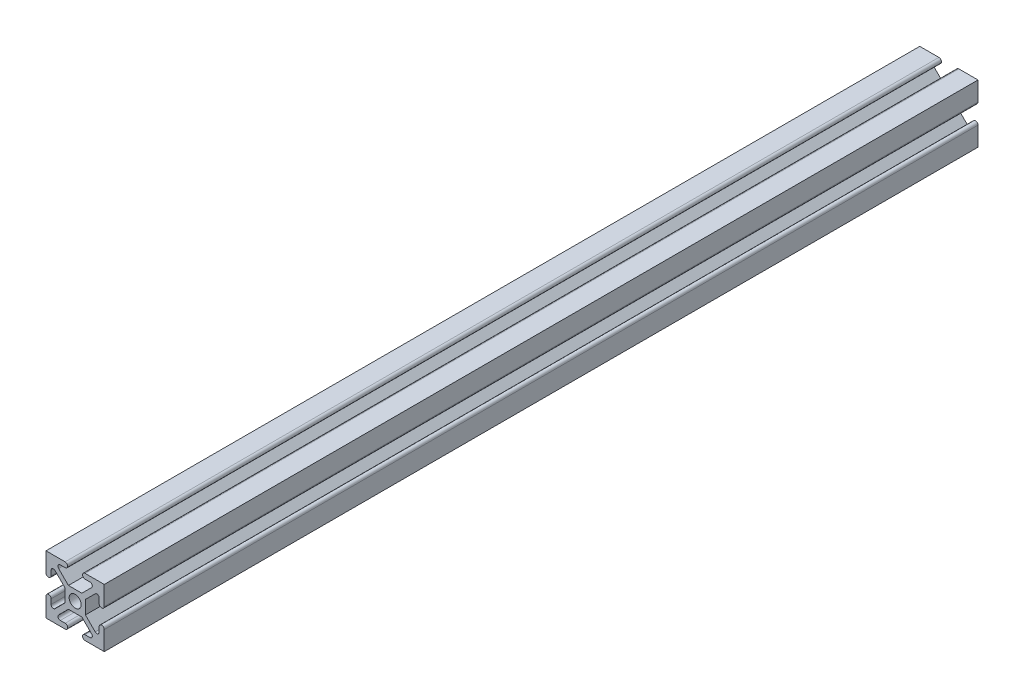
SolidWorks part; units mm, degrees
material "1060 Alloy"
ref_plane "Front Plane" through (0, 0, 0) normal (0, 0, 1) x (1, 0, 0)
ref_plane "Top Plane" through (0, 0, 0) normal (0, 1, 0) x (1, 0, 0)
ref_plane "Right Plane" through (0, 0, 0) normal (1, 0, 0) x (0, 0, -1)
sketch "Sketch1" plane through (0, 0, 0) normal (0, 0, 1) x (1, 0, 0)
  line L2 (-12.7, -12.7) -> (-4.3434, -12.7)
  line L3 (-4.3434, -10.4902) -> (-6.4748, -10.4902)
  line L4 (-7.1932, -8.7558) -> (-2.9332, -4.4958)
  line L5 (-2.9332, -4.4958) -> (2.9332, -4.4958)
  line L6 (2.9332, -4.4958) -> (7.1932, -8.7558)
  line L7 (6.4748, -10.4902) -> (4.3434, -10.4902)
  line L8 (4.3434, -12.7) -> (12.7, -12.7)
  line L11 (12.7, -12.7) -> (12.7, -4.3434)
  line L12 (10.4902, -4.3434) -> (10.4902, -6.4748)
  line L13 (8.7558, -7.1932) -> (4.4958, -2.9332)
  line L14 (4.4958, -2.9332) -> (4.4958, 2.9332)
  line L15 (4.4958, 2.9332) -> (8.7558, 7.1932)
  line L16 (10.4902, 6.4748) -> (10.4902, 4.3434)
  line L17 (12.7, 4.3434) -> (12.7, 12.7)
  line L20 (12.7, 12.7) -> (4.3434, 12.7)
  line L21 (4.3434, 10.4902) -> (6.4748, 10.4902)
  line L22 (7.1932, 8.7558) -> (2.9332, 4.4958)
  line L23 (2.9332, 4.4958) -> (-2.9332, 4.4958)
  line L24 (-2.9332, 4.4958) -> (-7.1932, 8.7558)
  line L25 (-6.4748, 10.4902) -> (-4.3434, 10.4902)
  line L26 (-4.3434, 12.7) -> (-12.7, 12.7)
  line L29 (-12.7, 12.7) -> (-12.7, 4.3434)
  line L30 (-10.4902, 4.3434) -> (-10.4902, 6.4748)
  line L31 (-8.7558, 7.1932) -> (-4.4958, 2.9332)
  line L32 (-4.4958, 2.9332) -> (-4.4958, -2.9332)
  line L33 (-4.4958, -2.9332) -> (-8.7558, -7.1932)
  line L34 (-10.4902, -6.4748) -> (-10.4902, -4.3434)
  line L35 (-12.7, -4.3434) -> (-12.7, -12.7)
  circle A0 centre (0, 0) radius 2.6035
  arc A6 (-4.3434, -12.7) -> (-4.3434, -10.4902) centre (-4.3434, -11.5951) ccw
  arc A7 (-6.4748, -10.4902) -> (-7.1932, -8.7558) centre (-6.4748, -9.4742) cw
  arc A10 (7.1932, -8.7558) -> (6.4748, -10.4902) centre (6.4748, -9.4742) cw
  arc A11 (4.3434, -10.4902) -> (4.3434, -12.7) centre (4.3434, -11.5951) ccw
  arc A17 (12.7, -4.3434) -> (10.4902, -4.3434) centre (11.5951, -4.3434) ccw
  arc A18 (10.4902, -6.4748) -> (8.7558, -7.1932) centre (9.4742, -6.4748) cw
  arc A21 (8.7558, 7.1932) -> (10.4902, 6.4748) centre (9.4742, 6.4748) cw
  arc A22 (10.4902, 4.3434) -> (12.7, 4.3434) centre (11.5951, 4.3434) ccw
  arc A28 (4.3434, 12.7) -> (4.3434, 10.4902) centre (4.3434, 11.5951) ccw
  arc A29 (6.4748, 10.4902) -> (7.1932, 8.7558) centre (6.4748, 9.4742) cw
  arc A32 (-7.1932, 8.7558) -> (-6.4748, 10.4902) centre (-6.4748, 9.4742) cw
  arc A33 (-4.3434, 10.4902) -> (-4.3434, 12.7) centre (-4.3434, 11.5951) ccw
  arc A39 (-12.7, 4.3434) -> (-10.4902, 4.3434) centre (-11.5951, 4.3434) ccw
  arc A40 (-10.4902, 6.4748) -> (-8.7558, 7.1932) centre (-9.4742, 6.4748) cw
  arc A43 (-8.7558, -7.1932) -> (-10.4902, -6.4748) centre (-9.4742, -6.4748) cw
  arc A44 (-10.4902, -4.3434) -> (-12.7, -4.3434) centre (-11.5951, -4.3434) ccw
  point P101 (-4.4958, 0)
  point P102 (0, 4.4958)
  point P103 (4.4958, 0)
  point P127 (0, -4.4958)
extrude "Boss-Extrude1" add sketch "Sketch1" against normal blind 381
